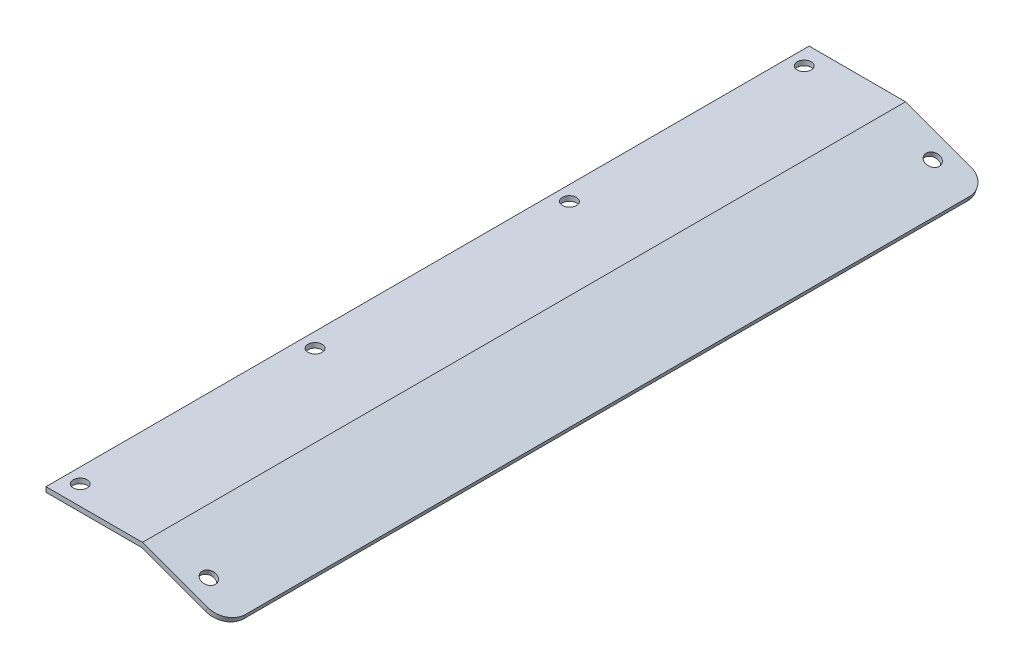
SolidWorks part; units mm, degrees
ref_plane "Front Plane" through (0, 0, 0) normal (0, 0, 1) x (1, 0, 0)
ref_plane "Top Plane" through (0, 0, 0) normal (0, 1, 0) x (1, 0, 0)
ref_plane "Right Plane" through (0, 0, 0) normal (1, 0, 0) x (0, 0, -1)
sketch "Sketch1" plane through (0, 0, 0) normal (0, 0, 1) x (1, 0, 0)
  line L0 (0, 0) -> (31.0189, 0)
  line L1 (31.0189, 0) -> (57.8706, -9.7732)
  line L2 (57.8706, -9.7732) -> (58.4135, -8.2815)
  line L3 (58.4135, -8.2815) -> (31.2988, 1.5875)
  line L4 (31.2988, 1.5875) -> (0, 1.5875)
  line L5 (0, 1.5875) -> (0, 0)
  line L9 (31.2819, -0.0957) -> (54.9047, -8.6937) construction
  dimension "D1" = 1.5875
  dimension "D2" = 1.5875
  dimension "D3" = 28.575
extrude "Boss-Extrude1" add sketch "Sketch1" along normal up to surface (247.65 mm away)
sketch "Sketch2" plane through (0, 1.5875, 0) normal (0, 1, 0) x (1, 0, 0)
  line L0 (0, -247.65) -> (0, 0) construction
  line L1 (31.2988, 0) -> (0, 0) construction
  line L2 (31.2988, -247.65) -> (0, -247.65) construction
  circle A0 centre (4.7625, -6.35) radius 2.286
  circle A1 centre (4.7625, -241.3) radius 2.286
  circle A2 centre (4.7625, -82.55) radius 2.286
  circle A3 centre (4.7625, -165.1) radius 2.286
  dimension "D3" = 4.572
  dimension "D1" = 4.7625
  dimension "D2" = 6.35
  dimension "D4" = 6.35
  dimension "D5" = 76.2
  dimension "D6" = 76.2
extrude "Cut-Extrude1" cut sketch "Sketch2" against normal through all
sketch "Sketch3" plane through (4.1715, 11.461, 0) normal (0.342, 0.9397, 0) x (0.9397, -0.342, 0)
  line L0 (57.7232, 0) -> (28.8683, 0) construction
  line L5 (57.7232, -247.65) -> (57.7232, 0) construction
  line L6 (57.7232, -247.65) -> (28.8683, -247.65) construction
  circle A0 centre (45.0232, -6.35) radius 2.286
  circle A1 centre (45.0232, -241.3) radius 2.286
  dimension "D3" = 4.572
  dimension "D1" = 6.35
  dimension "D2" = 12.7
  dimension "D4" = 6.35
extrude "Cut-Extrude2" cut sketch "Sketch3" against normal through all
fillet "Fillet1" radius 6.35 2 edges at (58.1421, -9.0273, 0) (58.1421, -9.0273, 247.65)
